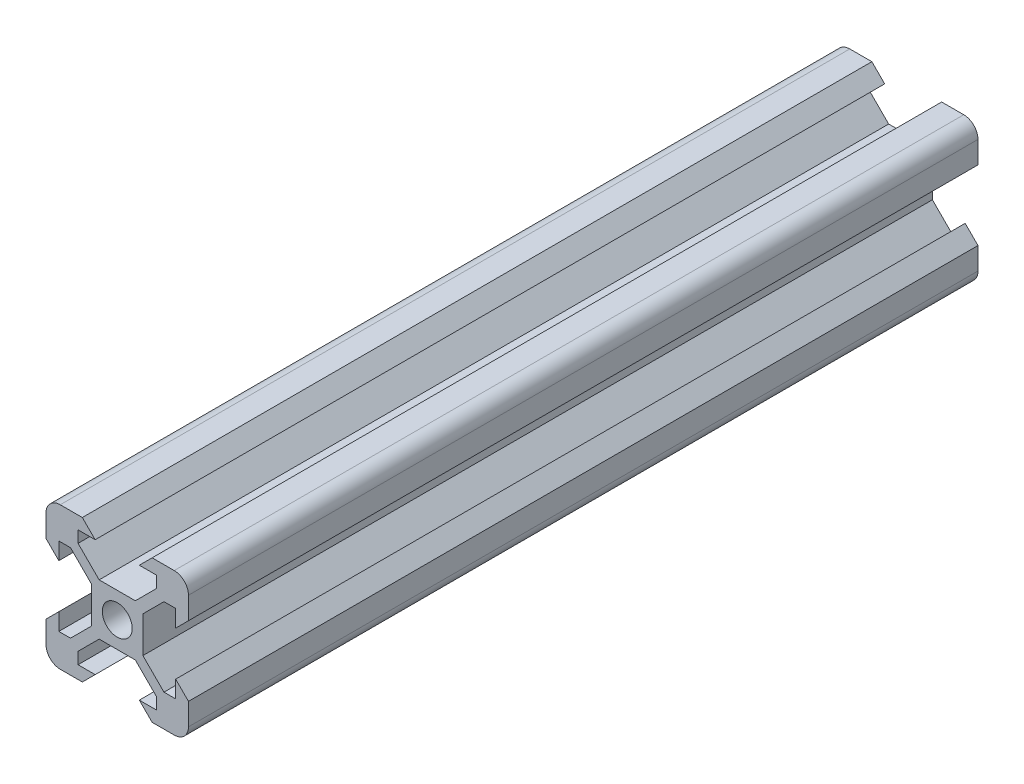
SolidWorks part; units mm, degrees
material "6061 Alloy"
ref_plane "Front Plane" through (0, 0, 0) normal (0, 0, 1) x (1, 0, 0)
ref_plane "Top Plane" through (0, 0, 0) normal (0, 1, 0) x (1, 0, 0)
ref_plane "Right Plane" through (0, 0, 0) normal (1, 0, 0) x (0, 0, -1)
sketch "Sketch1" plane through (0, 0, 0) normal (0, 0, 1) x (1, 0, 0)
  line L0 (-4.9, -10) -> (-5.5, -10)
  line L1 (-10, -10) -> (10, -10) construction
  line L2 (-10, -10) -> (-10, 10) construction
  line L3 (-10, 10) -> (10, 10) construction
  line L4 (10, -10) -> (10, 10) construction
  line L5 (-10, -10) -> (10, 10) construction
  line L6 (-10, 10) -> (10, -10) construction
  line L7 (-3.6, 3.6) -> (3.6, 3.6)
  line L8 (-3.6, 3.6) -> (-3.6, -3.6)
  line L9 (-3.6, -3.6) -> (3.6, -3.6)
  line L10 (3.6, 3.6) -> (3.6, -3.6)
  line L11 (-8, 10) -> (-5.5, 10)
  line L12 (-10, 8) -> (-10, 5.5)
  line L13 (-10, 5.5) -> (-5.5, 5.5)
  line L14 (-5.5, 10) -> (-5.5, 5.5)
  line L15 (8, 10) -> (5.5, 10)
  line L16 (10, 8) -> (10, 5.5)
  line L17 (10, 5.5) -> (5.5, 5.5)
  line L18 (5.5, 10) -> (5.5, 5.5)
  line L19 (8, -10) -> (5.5, -10)
  line L20 (10, -8) -> (10, -5.5)
  line L21 (10, -5.5) -> (5.5, -5.5)
  line L22 (5.5, -10) -> (5.5, -5.5)
  line L23 (-8, -10) -> (-5.5, -10)
  line L24 (-10, -8) -> (-10, -5.5)
  line L25 (-10, -5.5) -> (-5.5, -5.5)
  line L26 (-5.5, -10) -> (-5.5, -5.5)
  line L27 (-3.1, -8.2) -> (-4.9, -10)
  line L28 (-3.1, -8.2) -> (-5.5, -8.2)
  line L29 (4.9, -10) -> (5.5, -10)
  line L30 (3.1, -8.2) -> (4.9, -10)
  line L31 (3.1, -8.2) -> (5.5, -8.2)
  line L32 (-4.9, 10) -> (-5.5, 10)
  line L33 (-3.1, 8.2) -> (-4.9, 10)
  line L34 (-3.1, 8.2) -> (-5.5, 8.2)
  line L35 (4.9, 10) -> (5.5, 10)
  line L36 (0, 0) -> (17.4618, 0) construction
  line L37 (3.1, 8.2) -> (4.9, 10)
  line L38 (3.1, 8.2) -> (5.5, 8.2)
  line L39 (8.2, 3.1) -> (8.2, 5.5)
  line L40 (8.2, 3.1) -> (10, 4.9)
  line L41 (10, 4.9) -> (10, 5.5)
  line L42 (10, -4.9) -> (10, -5.5)
  line L43 (8.2, -3.1) -> (10, -4.9)
  line L44 (8.2, -3.1) -> (8.2, -5.5)
  line L57 (-8.2, -3.1) -> (-10, -4.9)
  line L58 (-10, -4.9) -> (-10, -5.5)
  line L61 (-8.2, -3.1) -> (-8.2, -5.5)
  line L62 (-8.2, 3.1) -> (-10, 4.9)
  line L63 (-10, 4.9) -> (-10, 5.5)
  line L66 (-8.2, 3.1) -> (-8.2, 5.5)
  line L67 (-2.7729, 2.7729) -> (-6.4508, 6.4508) construction
  line L68 (-2.2426, 3.3033) -> (-5.9205, 6.9812)
  line L69 (-3.3033, 2.2426) -> (-6.9812, 5.9205)
  line L70 (6.7372, 6.7372) -> (2.7729, 2.7729)
  line L71 (6.309, -6.309) -> (2.7729, -2.7729)
  line L72 (-2.8687, -2.8687) -> (-6.5971, -6.5971)
  line L73 (6.2069, 7.2675) -> (2.2426, 3.3033)
  line L74 (6.8393, -5.7786) -> (3.3033, -2.2426)
  line L75 (-3.399, -2.3384) -> (-7.1274, -6.0667)
  line L76 (7.2675, 6.2069) -> (3.3033, 2.2426)
  line L77 (5.7786, -6.8393) -> (2.2426, -3.3033)
  line L78 (-2.3384, -3.399) -> (-6.0667, -7.1274)
  circle A0 centre (0, 0) radius 2.1
  arc A1 (-8, -10) -> (-10, -8) centre (-8, -8) cw
  arc A2 (8, -10) -> (10, -8) centre (8, -8) ccw
  arc A3 (8, 10) -> (10, 8) centre (8, 8) cw
  arc A4 (-8, 10) -> (-10, 8) centre (-8, 8) ccw
  point P0 (0, 0)
  dimension "D3" = 4.2
  dimension "D12" = 2
  dimension "D1" = 20
  dimension "D4" = 6.4
  dimension "D5" = 6.4
  dimension "D6" = 6.4
  dimension "D7" = 6.4
  dimension "D8" = 4.5
  dimension "D9" = 4.5
  dimension "D10" = 4.5
  dimension "D11" = 4.5
  dimension "D13" = 45
  dimension "D19" = 45
  dimension "D20" = 6.2
  dimension "D23" = 1.8
  dimension "D24" = 1.8
  dimension "D28" = 0.75
  dimension "D26" = 0.75
  dimension "D27" = 0.75
  dimension "D29" = 0.75
extrude "Boss-Extrude1" add sketch "Sketch1" along normal blind 110.83
